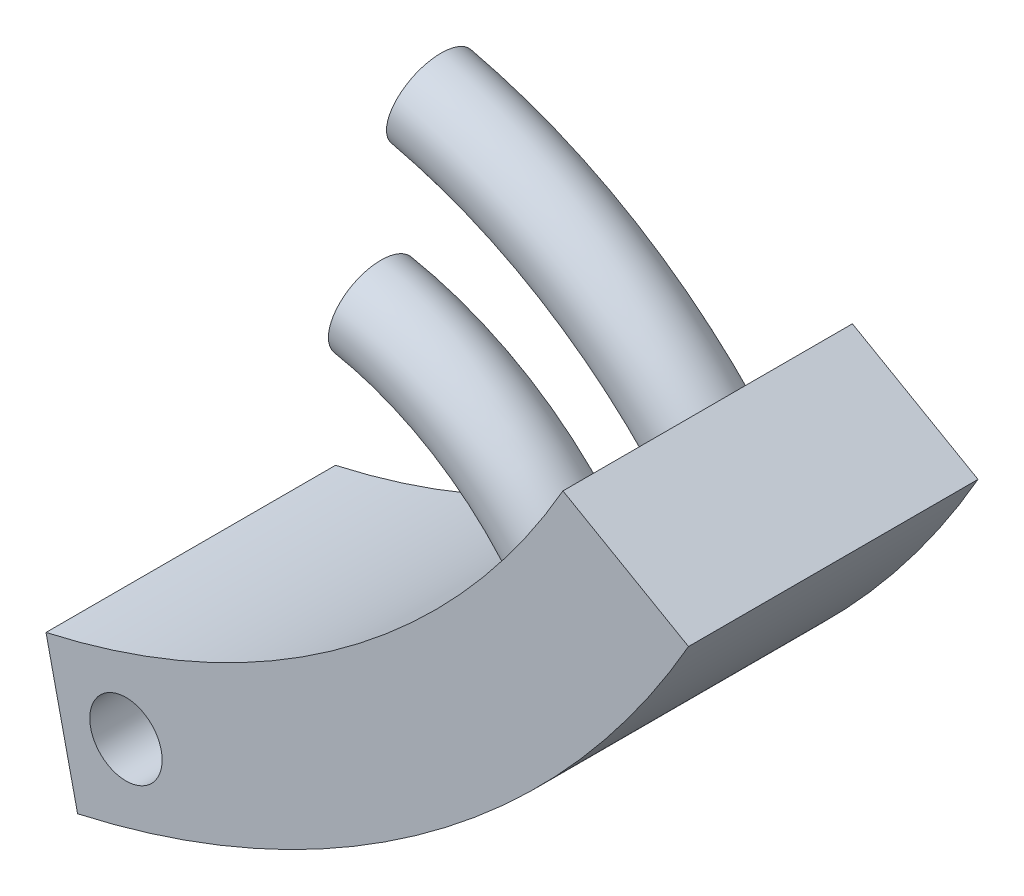
SolidWorks part; units mm, degrees
material "Balsa"
ref_plane "Front Plane" through (0, 0, 0) normal (0, 0, 1) x (1, 0, 0)
ref_plane "Top Plane" through (0, 0, 0) normal (0, 1, 0) x (1, 0, 0)
ref_plane "Right Plane" through (0, 0, 0) normal (1, 0, 0) x (0, 0, -1)
sketch "Sketch1" plane through (0, 0, 0) normal (0, 0, 1) x (1, 0, 0)
  line L0 (0, 0) -> (4.365, -19.5179)
  line L1 (71.4284, 52.6491) -> (88.7804, 42.7038)
  arc A0 (0, 0) -> (71.4284, 52.6491) centre (-24.0075, 107.3482) ccw
  arc A1 (4.365, -19.5179) -> (88.7804, 42.7038) centre (-24.0075, 107.3482) ccw
  dimension "D1" = 110
  dimension "D2" = 20
extrude "Boss-Extrude1" add sketch "Sketch1" along normal blind 40
sketch "Sketch3" plane through (0, 0, 40) normal (0, 0, 1) x (1, 0, 0)
  circle A0 centre (11.0481, -7.248) radius 5
  dimension "D1" = 10
extrude "Cut-Extrude1" cut sketch "Sketch3" against normal through all both and the other way through all
ref_plane "Plane1" through (0, 0, 15) normal (0, 0, 1) x (1, 0, 0)
sketch "Sketch32" plane through (0, 0, 15) normal (0, 0, 1) x (1, 0, 0)
  arc A1 (65.3953, 44.4374) -> (28.2, 65.7644) centre (11.0481, -7.248) ccw
  dimension "D2" = 75
sweep "Sweep3" add path "Sketch32" circular profile diameter 12 parameters "D3"=12
sketch "Sketch48" plane through (0, 0, 15) normal (0, 0, 1) x (1, 0, 0)
  arc A1 (51.1368, 14.0423) -> (20.1268, 36.7887) centre (11.5684, -7.39) ccw
  dimension "D1" = 45
sweep "Sweep4" add path "Sketch48" circular profile diameter 12 parameters "D3"=12
